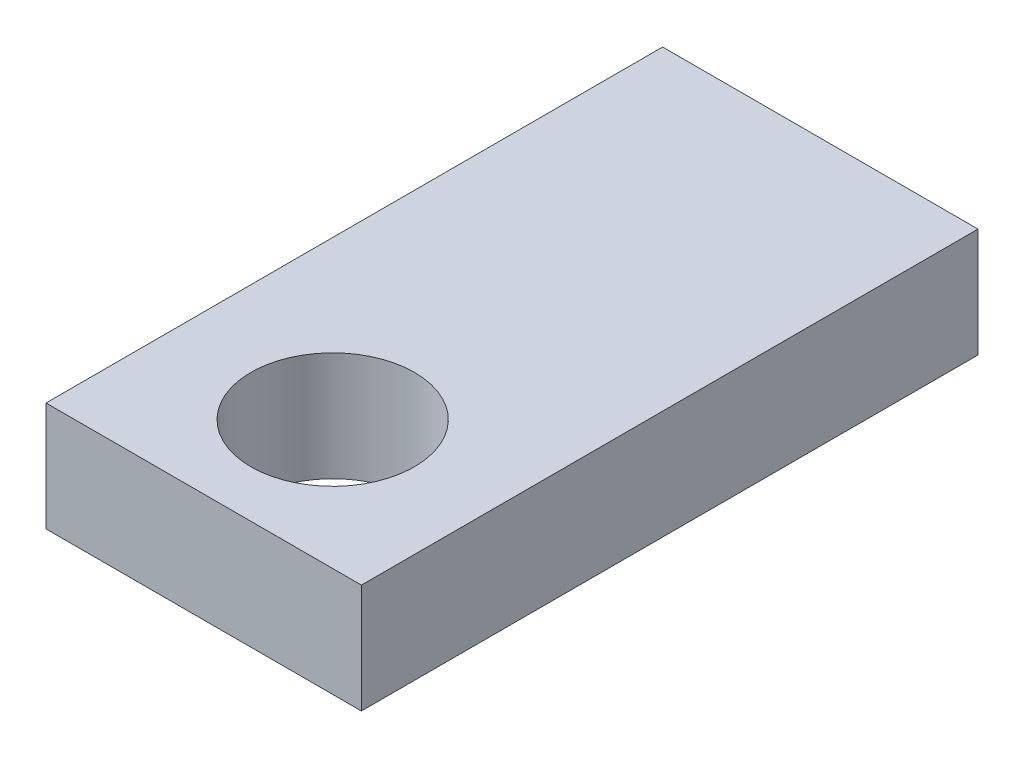
SolidWorks part; units mm, degrees
ref_plane "Front Plane" through (0, 0, 0) normal (0, 0, 1) x (1, 0, 0)
ref_plane "Top Plane" through (0, 0, 0) normal (0, 1, 0) x (1, 0, 0)
ref_plane "Right Plane" through (0, 0, 0) normal (1, 0, 0) x (0, 0, -1)
sketch "Sketch1" plane through (0, 0, 0) normal (0, 1, 0) x (1, 0, 0)
  line L0 (11.5687, 17.4647) -> (11.5687, -17.4647)
  line L1 (-11.5687, 17.4647) -> (11.5687, 17.4647)
  line L2 (-11.5687, 17.4647) -> (-11.5687, -17.4647)
  line L3 (-11.5687, -17.4647) -> (11.5687, -17.4647)
  line L4 (0, 17.4647) -> (0, -17.4647) construction
  circle A0 centre (0, -8.0024) radius 1.5
  circle A1 centre (0, -8.0024) radius 6
extrude "Boss-Extrude1" add sketch "Sketch1" along normal blind 8 contours L1 L4 A1 L3 L0 | L4 L1 L2 L3 A1
sketch "Sketch2" plane through (0, 0, 0) normal (0, -1, 0) x (1, 0, 0)
  line L1 (-11.5687, -17.4647) -> (11.5687, -17.4647)
  line L2 (-11.5687, -17.4647) -> (-11.5687, -27.7714)
  line L3 (-11.5687, -27.7714) -> (11.5687, -27.7714)
  line L4 (11.5687, -17.4647) -> (11.5687, -27.7714)
extrude "Boss-Extrude2" add sketch "Sketch2" against normal blind 8
